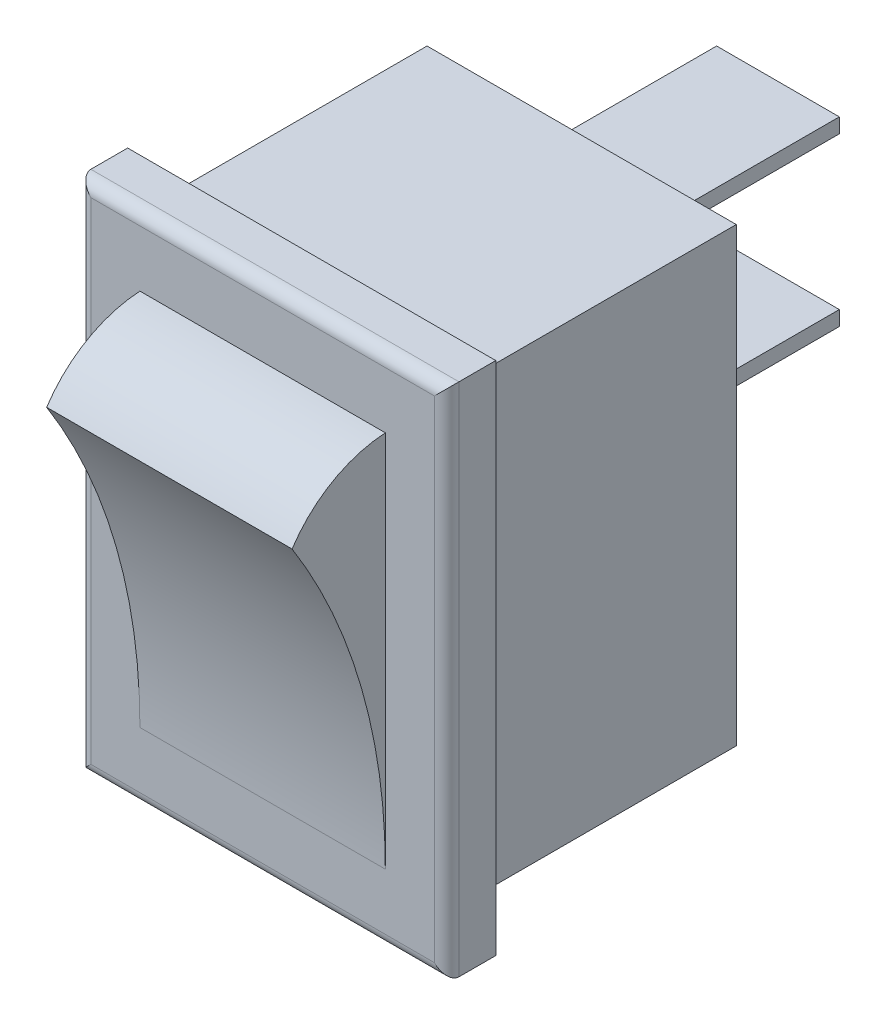
SolidWorks part; units mm, degrees
ref_plane "Спереди" through (0, 0, 0) normal (0, 0, 1) x (1, 0, 0)
ref_plane "Сверху" through (0, 0, 0) normal (0, 1, 0) x (1, 0, 0)
ref_plane "Справа" through (0, 0, 0) normal (1, 0, 0) x (0, 0, -1)
sketch "Эскиз1" plane through (0, 0, 0) normal (0, 0, 1) x (1, 0, 0)
  line L1 (-6.3, -9.2) -> (6.3, -9.2)
  line L2 (-6.3, -9.2) -> (-6.3, 9.2)
  line L3 (-6.3, 9.2) -> (6.3, 9.2)
  line L4 (6.3, -9.2) -> (6.3, 9.2)
  line L5 (-6.3, -9.2) -> (6.3, 9.2) construction
  line L6 (-6.3, 9.2) -> (6.3, -9.2) construction
  point P0 (0, 0)
  dimension "D1" = 12.6
  dimension "D2" = 18.4
extrude "Бобышка-Вытянуть1" add sketch "Эскиз1" along normal blind 11
sketch "Эскиз2" plane through (0, 0, 11) normal (0, 0, 1) x (1, 0, 0)
  line L1 (-7.5, -10.5) -> (7.5, -10.5)
  line L2 (-7.5, -10.5) -> (-7.5, 10.5)
  line L3 (-7.5, 10.5) -> (7.5, 10.5)
  line L4 (7.5, -10.5) -> (7.5, 10.5)
  line L5 (-7.5, -10.5) -> (7.5, 10.5) construction
  line L6 (-7.5, 10.5) -> (7.5, -10.5) construction
  point P0 (0, 0)
  dimension "D1" = 15
  dimension "D2" = 21
extrude "Бобышка-Вытянуть2" add sketch "Эскиз2" along normal blind 2
fillet "Скругление1" radius 0.5 4 edges at (0, -10.5, 13) (-7.5, 0, 13) (0, 10.5, 13) (7.5, 0, 13)
sketch "Эскиз3" plane through (0, 0, 0) normal (1, 0, 0) x (0, 0, -1)
  line L0 (-13, -10) -> (-13, 10) construction
  line L1 (-13, -7.7) -> (-13, 7.7)
  line L2 (-12.5, -10.5) -> (-11, -10.5) construction
  line L3 (-12.5, 10.5) -> (-11, 10.5) construction
  arc A0 (-13, -7.7) -> (-16.8, 5.5) centre (-37.8263, -7.7) ccw
  arc A1 (-16.8, 5.5) -> (-13, 7.7) centre (-12.7107, 2.8185) cw
  point P7 (-16.0007, 4.2984)
  dimension "D1" = 2.8
  dimension "D2" = 3.8
  dimension "D3" = 2.2
  dimension "D4" = 2.8
extrude "Бобышка-Вытянуть3" add sketch "Эскиз3" along normal mid plane 10
sketch "Эскиз4" plane through (0, 0, 0) normal (0, 0, -1) x (-1, 0, 0)
  line L1 (2.5, -0.3) -> (-2.5, -0.3)
  line L2 (2.5, -0.3) -> (2.5, 0.3)
  line L3 (2.5, 0.3) -> (-2.5, 0.3)
  line L4 (-2.5, -0.3) -> (-2.5, 0.3)
  line L5 (2.5, -0.3) -> (-2.5, 0.3) construction
  line L6 (2.5, 0.3) -> (-2.5, -0.3) construction
  point P0 (0, 0)
  dimension "D1" = 0.6
  dimension "D2" = 5
extrude "Бобышка-Вытянуть4" add sketch "Эскиз4" along normal blind 8
pattern_linear "Линейный массив1" count 2 spacing 6.8 along (0, 1, 0) of "Бобышка-Вытянуть4"
